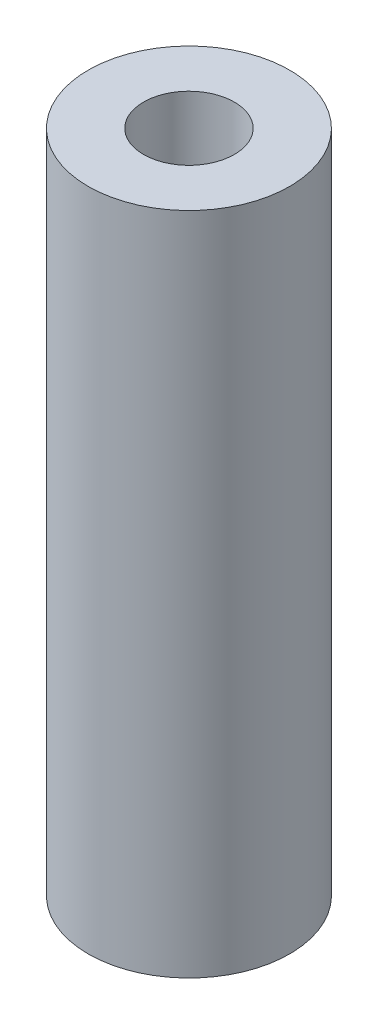
SolidWorks part; units mm, degrees
material "1060 Alloy"
ref_plane "Front Plane" through (0, 0, 0) normal (0, 0, 1) x (1, 0, 0)
ref_plane "Top Plane" through (0, 0, 0) normal (0, 1, 0) x (1, 0, 0)
ref_plane "Right Plane" through (0, 0, 0) normal (1, 0, 0) x (0, 0, -1)
sketch "Sketch1" plane through (0, 0, 0) normal (0, 1, 0) x (1, 0, 0)
  circle A0 centre (0, 0) radius 3
  dimension "D1" = 6
extrude "Boss-Extrude1" add sketch "Sketch1" along normal blind 19.79
hole_wizard "#6-32 Tapped Hole1" positions "Sketch2" profile "Sketch3" tap size "#6-32" standard "ANSI Inch"
sketch "Sketch2" plane through (0, 19.79, 0) normal (0, 1, 0) x (1, 0, 0)
  point P0 (0, 0)
sketch "Sketch3" plane through (0, 19.79, 0) normal (1, 0, 0) x (0, 0, 1)
  line L0 (0, 0) -> (0, 7.8127)
  line L1 (0, 7.8127) -> (1.3525, 7)
  line L2 (1.3525, 7) -> (1.3525, 0)
  line L5 (1.3525, 0) -> (0, 0)
  line L10 (0, 7.8127) -> (-1.3526, 7) construction
  line L11 (0, -6.35) -> (0, 107.95) construction
  dimension "Tap Drill Dia." = 2.7051
  dimension "Tap Drill Depth" = 7
  dimension "Drill Angle" = 118
cosmetic thread "Hole Thread1"
hole_wizard "#6-32 Tapped Hole2" positions "Sketch4" profile "Sketch5" tap size "#6-32" standard "ANSI Inch"
sketch "Sketch4" plane through (0, 0, 0) normal (0, -1, 0) x (-1, 0, 0)
  point P0 (0, 0)
sketch "Sketch5" plane through (0, 0, 0) normal (1, 0, 0) x (0, 0, -1)
  line L0 (0, 0) -> (0, 7.8127)
  line L1 (0, 7.8127) -> (1.3525, 7)
  line L2 (1.3525, 7) -> (1.3525, 0)
  line L5 (1.3525, 0) -> (0, 0)
  line L10 (0, 7.8127) -> (-1.3526, 7) construction
  line L11 (0, -6.35) -> (0, 107.95) construction
  dimension "Tap Drill Dia." = 2.7051
  dimension "Tap Drill Depth" = 7
  dimension "Drill Angle" = 118
cosmetic thread "Hole Thread2"
